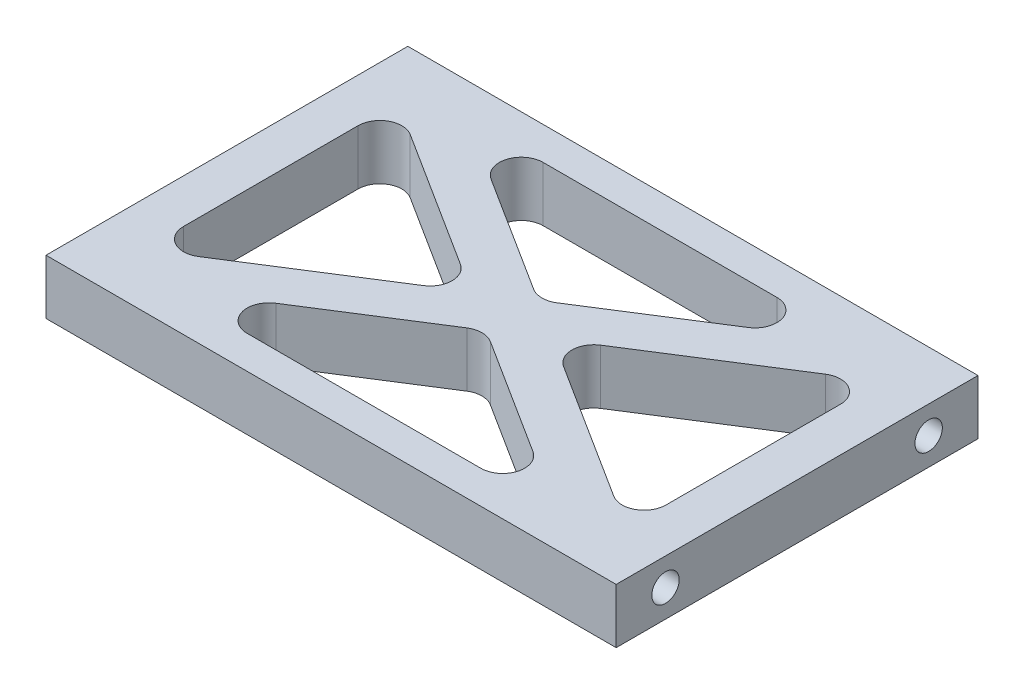
SolidWorks part; units mm, degrees
ref_plane "Front" through (0, 0, 0) normal (0, 0, 1) x (1, 0, 0)
ref_plane "Top" through (0, 0, 0) normal (0, 1, 0) x (1, 0, 0)
ref_plane "Right" through (0, 0, 0) normal (1, 0, 0) x (0, 0, -1)
sketch "Sketch1" plane through (0, 0, 0) normal (0, 1, 0) x (1, 0, 0)
  line L0 (0, 16.5) -> (52, 16.5) construction
  line L1 (0, 0) -> (52, 0)
  line L2 (0, 0) -> (0, 33)
  line L3 (0, 33) -> (52, 33)
  line L4 (52, 0) -> (52, 33)
  line L5 (26, 33) -> (26, 0) construction
  line L6 (0, 33) -> (52, 0) construction
  line L7 (52, 33) -> (0, 0) construction
  line L8 (4, 28.0928) -> (4, 4.9072)
  line L9 (4, 4.9072) -> (22.2674, 16.5)
  line L10 (22.2674, 16.5) -> (4, 28.0928)
  line L11 (26, 14.1313) -> (8.4598, 3)
  line L12 (8.4598, 3) -> (43.5402, 3)
  line L13 (43.5402, 3) -> (26, 14.1313)
  line L14 (48, 4.9072) -> (29.7326, 16.5)
  line L15 (29.7326, 16.5) -> (48, 28.0928)
  line L16 (48, 28.0928) -> (48, 4.9072)
  line L17 (8.4598, 30) -> (43.5402, 30)
  line L18 (43.5402, 30) -> (26, 18.8687)
  line L19 (26, 18.8687) -> (8.4598, 30)
  point P15 (26, 13.1197)
  dimension "D1" = 52
  dimension "D2" = 33
  dimension "D3" = 4
  dimension "D4" = 3
  dimension "D5" = 2
  dimension "D6" = 2
extrude "Boss-Extrude1" add sketch "Sketch1" along normal blind 5
fillet "Fillet1" radius 2 12 edges at (48, 2.5, -4.9072) (48, 2.5, -28.0928) (43.5402, 2.5, -30) (8.4598, 2.5, -30) (4, 2.5, -28.0928) (4, 2.5, -4.9072) (29.7326, 2.5, -16.5) (22.2674, 2.5, -16.5) (26, 2.5, -18.8687) (26, 2.5, -14.1313) (43.5402, 2.5, -3) (8.4598, 2.5, -3)
sketch "Sketch2" plane through (52, 0, 0) normal (1, 0, 0) x (0, 0, -1)
  line L0 (0, 2.5) -> (33, 2.5) construction
  line L1 (0, 5) -> (0, 0) construction
  line L2 (33, 5) -> (33, 0) construction
  line L3 (16.5, 5) -> (16.5, 0) construction
  line L4 (0, 5) -> (33, 5) construction
  line L5 (0, 0) -> (33, 0) construction
  circle A0 centre (4.5, 2.5) radius 1.25
  circle A1 centre (28.5, 2.5) radius 1.25
  dimension "D1" = 2.5
  dimension "D2" = 12
extrude "Cut-Extrude1" cut sketch "Sketch2" against normal blind 12
ref_plane "Plane1" through (26, 0, 0) normal (1, 0, 0) x (0, 0, -1)
mirror "Mirror1" about plane through (26, 0, 0) normal (1, 0, 0) of "Cut-Extrude1"
